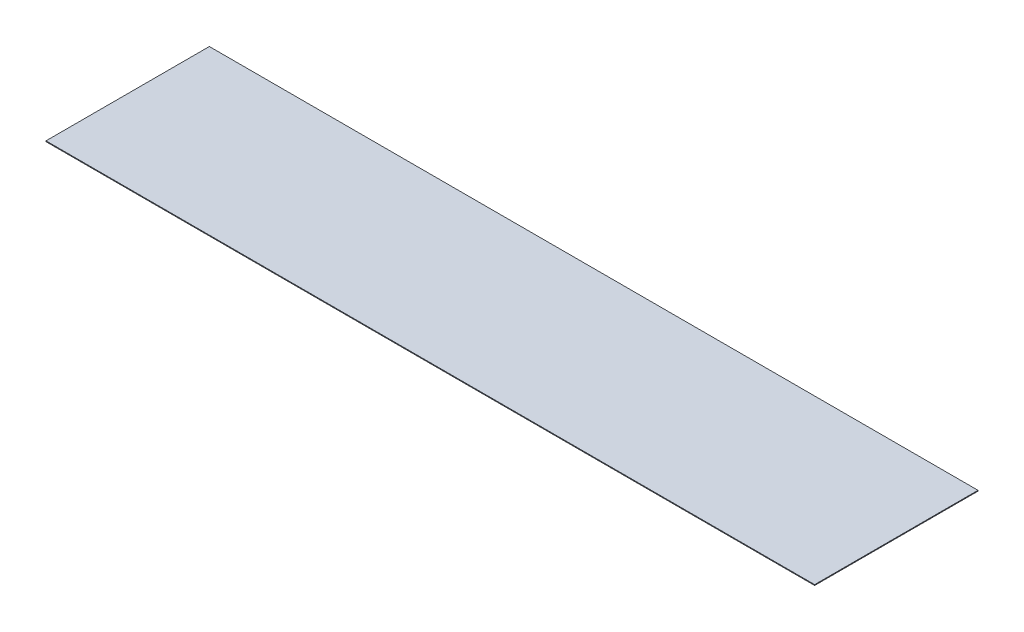
SolidWorks part; units mm, degrees
ref_plane "Спереди" through (0, 0, 0) normal (0, 0, 1) x (1, 0, 0)
ref_plane "Сверху" through (0, 0, 0) normal (0, 1, 0) x (1, 0, 0)
ref_plane "Справа" through (0, 0, 0) normal (1, 0, 0) x (0, 0, -1)
other "Configuration Table"
sketch "Эскиз1" plane through (0, 0, 0) normal (0, 1, 0) x (1, 0, 0)
  line L1 (500, 106.25) -> (-500, 106.25)
  line L2 (500, 106.25) -> (500, -106.25)
  line L3 (500, -106.25) -> (-500, -106.25)
  line L4 (-500, 106.25) -> (-500, -106.25)
  line L5 (500, 106.25) -> (-500, -106.25) construction
  line L6 (500, -106.25) -> (-500, 106.25) construction
  point P0 (0, 0)
extrude "Бобышка-Вытянуть1" add sketch "Эскиз1" along normal blind 1
